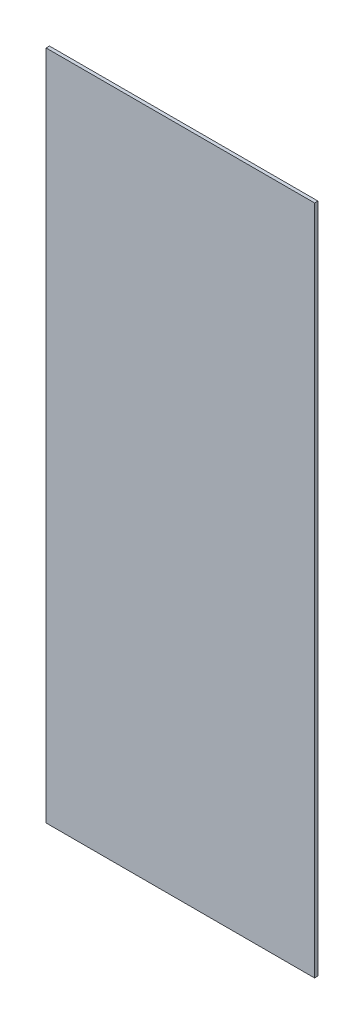
SolidWorks part; units mm, degrees
ref_plane "Front Plane" through (0, 0, 0) normal (0, 0, 1) x (1, 0, 0)
ref_plane "Top Plane" through (0, 0, 0) normal (0, 1, 0) x (1, 0, 0)
ref_plane "Right Plane" through (0, 0, 0) normal (1, 0, 0) x (0, 0, -1)
sketch "Sketch1" plane through (0, 0, 0) normal (0, 0, 1) x (1, 0, 0)
  line L1 (-80, -200) -> (80, -200)
  line L2 (-80, -200) -> (-80, 200)
  line L3 (-80, 200) -> (80, 200)
  line L4 (80, -200) -> (80, 200)
  line L5 (-80, -200) -> (80, 200) construction
  line L6 (-80, 200) -> (80, -200) construction
  point P0 (0, 0)
  dimension "D1" = 400
  dimension "D2" = 160
extrude "Boss-Extrude1" add sketch "Sketch1" along normal blind 2
